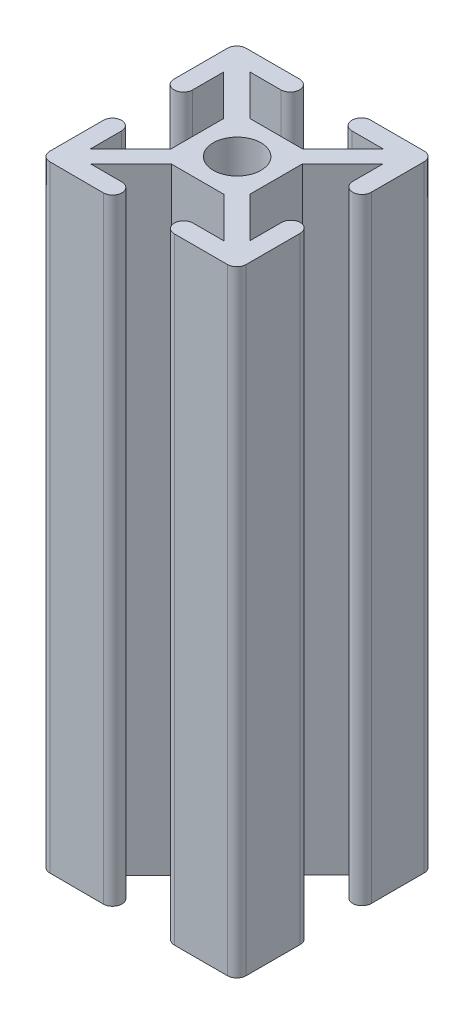
SolidWorks part; units mm, degrees
ref_plane "Front Plane" through (0, 0, 0) normal (0, 0, 1) x (1, 0, 0)
ref_plane "Top Plane" through (0, 0, 0) normal (0, 1, 0) x (1, 0, 0)
ref_plane "Right Plane" through (0, 0, 0) normal (1, 0, 0) x (0, 0, -1)
sketch "Sketch1" plane through (0, 0, 0) normal (0, 1, 0) x (1, 0, 0)
  line L0 (-7.576, 17.6853) -> (-7.576, 19.1103) construction
  line L1 (11.4769, 1.5353) -> (16.2019, 1.5353)
  line L2 (-9.001, 27.2603) -> (-9.001, 19.1103)
  line L3 (-7.576, 28.6853) -> (0.574, 28.6853)
  line L4 (11.424, 28.6853) -> (19.574, 28.6853)
  line L5 (-4.0981, 1.5353) -> (0.6269, 1.5353)
  line L6 (-0.001, 17.6853) -> (-0.001, 9.6853)
  line L7 (-8.9481, 8.2603) -> (-8.9481, 0.1103)
  line L8 (-7.5495, -1.2883) -> (0.6269, -1.3147)
  line L9 (20.999, 27.2603) -> (20.999, 19.214)
  line L10 (-6.151, 23.8353) -> (-6.151, 19.1103)
  line L11 (20.999, 8.364) -> (20.999, 0.1103)
  line L12 (1.999, 27.2603) -> (0.574, 27.2603) construction
  line L13 (11.4769, -1.3147) -> (19.574, -1.3147)
  line L14 (-4.151, 25.8353) -> (0.574, 25.8353)
  line L15 (-6.151, 8.2603) -> (-6.151, 3.5353)
  line L16 (9.999, 27.2603) -> (11.424, 27.2603) construction
  line L17 (11.424, 25.8353) -> (16.149, 25.8353)
  line L18 (19.574, 17.789) -> (19.574, 19.214) construction
  line L19 (1.999, 19.6853) -> (-4.151, 25.8353)
  line L20 (18.149, 23.8353) -> (18.149, 19.214)
  line L21 (19.574, 9.789) -> (19.574, 8.364) construction
  line L22 (-0.001, 17.6853) -> (-6.151, 23.8353)
  line L23 (18.149, 8.364) -> (18.149, 3.5353)
  line L24 (10.0519, 0.1103) -> (11.4769, 0.1103) construction
  line L25 (-0.001, 9.6853) -> (-6.151, 3.5353)
  line L26 (1.999, 19.6853) -> (9.999, 19.6853)
  line L27 (9.999, 19.6853) -> (16.149, 25.8353)
  line L28 (-7.5495, 9.6853) -> (-7.5495, 8.2603) construction
  line L29 (-4.0981, 1.5353) -> (2.0519, 7.6853)
  line L30 (2.0519, 7.6853) -> (10.0519, 7.6853)
  line L31 (10.0519, 7.6853) -> (16.2019, 1.5353)
  line L32 (2.0519, 0.1103) -> (0.6269, 0.1103) construction
  line L33 (11.999, 9.6853) -> (18.149, 3.5353)
  line L34 (11.999, 17.6853) -> (18.149, 23.8353)
  line L35 (11.999, 17.6853) -> (11.999, 9.6853)
  circle A0 centre (6.0519, 13.6853) radius 3.645
  arc A1 (-9.001, 19.1103) -> (-6.151, 19.1103) centre (-7.576, 19.1103) ccw
  arc A2 (0.574, 25.8353) -> (0.574, 28.6853) centre (0.574, 27.2603) ccw
  arc A3 (11.424, 28.6853) -> (11.424, 25.8353) centre (11.424, 27.2603) ccw
  arc A4 (18.149, 19.214) -> (20.999, 19.214) centre (19.574, 19.214) ccw
  arc A5 (20.999, 8.364) -> (18.149, 8.364) centre (19.574, 8.364) ccw
  arc A6 (11.4769, 1.5353) -> (11.4769, -1.3147) centre (11.4769, 0.1103) ccw
  arc A7 (-6.151, 8.2603) -> (-8.9481, 8.2603) centre (-7.5495, 8.2603) ccw
  arc A8 (0.6269, -1.3147) -> (0.6269, 1.5353) centre (0.6269, 0.1103) ccw
  arc A9 (-8.9481, 0.1103) -> (-7.5495, -1.2883) centre (-7.5495, 0.1103) ccw
  arc A10 (19.574, -1.3147) -> (20.999, 0.1103) centre (19.574, 0.1103) ccw
  arc A11 (20.999, 27.2603) -> (19.574, 28.6853) centre (19.574, 27.2603) ccw
  arc A12 (-7.576, 28.6853) -> (-9.001, 27.2603) centre (-7.576, 27.2603) ccw
  dimension "D1" = 7.29
  dimension "D2" = 1.425
  dimension "D3" = 1.425
  dimension "D4" = 1.425
  dimension "D5" = 1.425
  dimension "D6" = 1.425
  dimension "D7" = 1.425
  dimension "D8" = 1.425
extrude "Boss-Extrude1" add sketch "Sketch1" along normal blind 93.98
sketch "Sketch2" plane through (11.999, 0, 0) normal (1, 0, 0) x (0, 0, -1)
  line L0 (9.6853, 93.98) -> (17.6853, 93.98) construction
  line L1 (9.6853, 0) -> (17.6853, 0) construction
  circle A0 centre (13.6853, 75.14) radius 4
  circle A1 centre (13.6853, 18.84) radius 4
  point P4 (13.6853, 93.98)
  point P10 (13.6853, 0)
  dimension "D2" = 8
  dimension "D4" = 8
  dimension "D1" = 0
  dimension "D3" = 18.84
  dimension "D5" = 18.84
extrude "Cut-Extrude1" cut sketch "Sketch2" against normal blind 93.98
